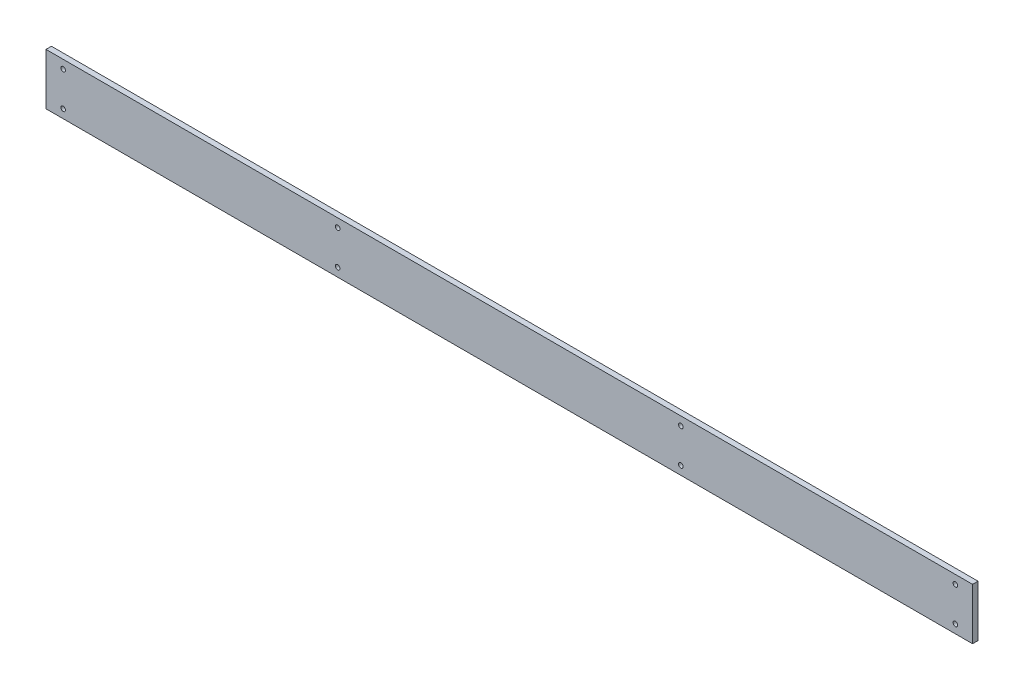
SolidWorks part; units mm, degrees
ref_plane "Front Plane" through (0, 0, 0) normal (0, 0, 1) x (1, 0, 0)
ref_plane "Top Plane" through (0, 0, 0) normal (0, 1, 0) x (1, 0, 0)
ref_plane "Right Plane" through (0, 0, 0) normal (1, 0, 0) x (0, 0, -1)
sketch "Sketch3" plane through (0, 0, 0) normal (0, 0, 1) x (1, 0, 0)
  line L1 (-270, 15) -> (270, 15)
  line L2 (-270, 15) -> (-270, -15)
  line L3 (-270, -15) -> (270, -15)
  line L4 (270, 15) -> (270, -15)
  line L5 (-270, 15) -> (270, -15) construction
  line L6 (-270, -15) -> (270, 15) construction
  point P0 (0, 0)
  dimension "D1" = 540
  dimension "D2" = 30
extrude "Boss-Extrude3" add sketch "Sketch3" along normal blind 3.18
sketch "Sketch4" plane through (0, 0, 3.18) normal (0, 0, 1) x (1, 0, 0)
  line L0 (270, 0) -> (-270, 0) construction
  line L1 (270, -15) -> (270, 15) construction
  line L2 (-270, 15) -> (-270, -15) construction
  line L3 (0, 15) -> (0, 0) construction
  line L4 (270, 15) -> (-270, 15) construction
  line L5 (0, 0) -> (0, -15) construction
  line L6 (-270, -15) -> (270, -15) construction
  line L7 (270, 15) -> (270, 0) construction
  line L8 (270, 0) -> (270, -15) construction
  line L9 (260, 15) -> (260, 0) construction
  line L12 (260, 10) -> (270, 10) construction
  circle A0 centre (260, 10) radius 1.35
  dimension "D2" = 2.7
  dimension "D3" = 10
  dimension "D1" = 5
extrude "Cut-Extrude1" cut sketch "Sketch4" against normal up to next
mirror "Mirror1" about plane through (0, 0, 0) normal (0, 1, 0) of "Cut-Extrude1"
mirror "Mirror2" about plane through (0, 0, 0) normal (1, 0, 0) of "Mirror1", "Cut-Extrude1"
sketch "Sketch5" plane through (0, 0, 3.18) normal (0, 0, 1) x (1, 0, 0)
  line L0 (0, -10) -> (100, -10) construction
  line L1 (-270, -15) -> (270, -15) construction
  circle A0 centre (100, -10) radius 1.35
  dimension "D2" = 2.7
  dimension "D1" = 100
  dimension "D3" = 5
extrude "Cut-Extrude2" cut sketch "Sketch5" against normal up to next
mirror "Mirror3" about plane through (0, 0, 0) normal (1, 0, 0) of "Cut-Extrude2"
mirror "Mirror4" about plane through (0, 0, 0) normal (0, 1, 0) of "Mirror3", "Cut-Extrude2"
